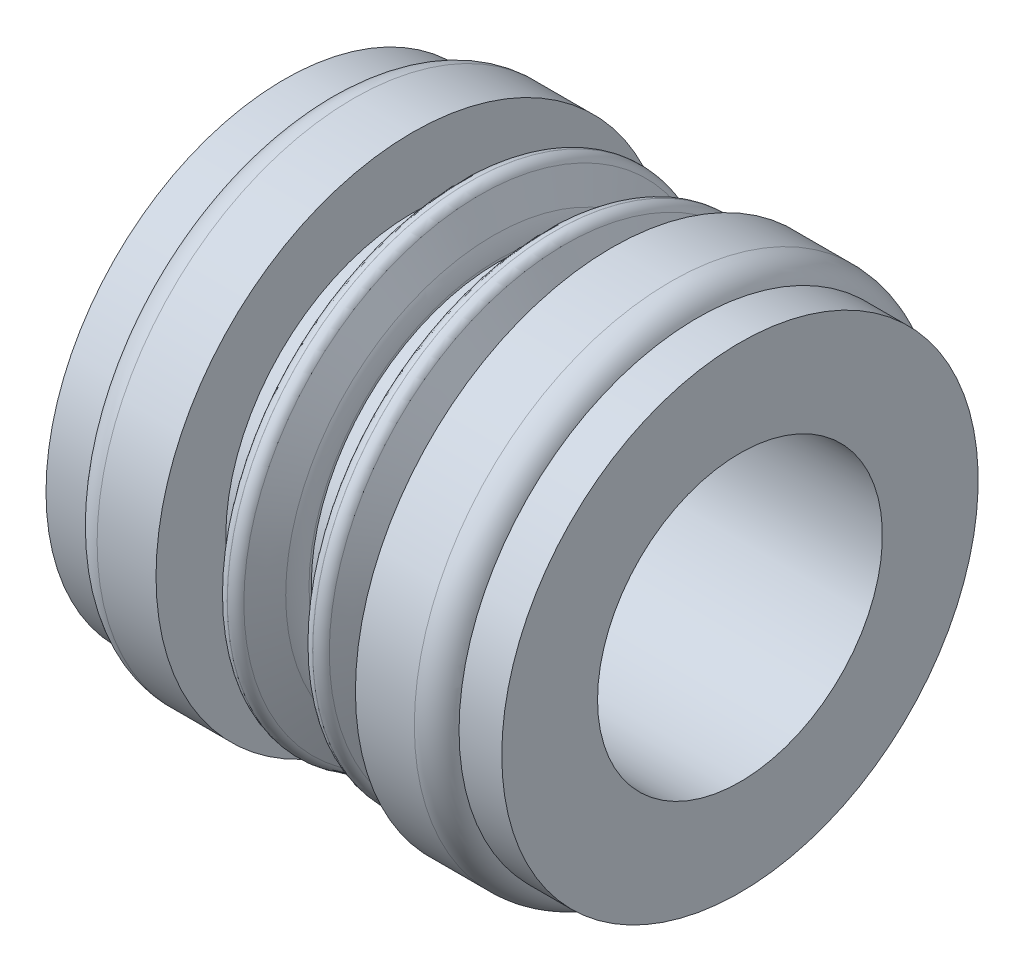
SolidWorks part; units mm, degrees
ref_plane "Front Plane" through (0, 0, 0) normal (0, 0, 1) x (1, 0, 0)
ref_plane "Top Plane" through (0, 0, 0) normal (0, 1, 0) x (1, 0, 0)
ref_plane "Right Plane" through (0, 0, 0) normal (1, 0, 0) x (0, 0, -1)
sketch "Sketch2" plane through (0, 0, 0) normal (0, 1, 0) x (1, 0, 0)
  line L0 (-34.5905, 0) -> (37.6381, 0) construction
  line L1 (-8, 5) -> (8, 5)
  line L2 (-8, 5) -> (-8, 8.3622)
  line L3 (-8, 8.3622) -> (-6.5, 8.3622)
  line L5 (-5.5679, 9) -> (-3.5, 9)
  line L6 (-3.5, 9) -> (-3.5, 6.55)
  line L7 (-3.5, 6.55) -> (-2.5, 6.55)
  line L8 (-2.5, 6.55) -> (-2.5, 6.6293)
  line L9 (-1.5013, 8.5) -> (-1.4987, 8.5)
  line L10 (-0.5, 6.6293) -> (-0.5, 6.55)
  line L11 (-0.5, 6.55) -> (0.5, 6.55)
  line L12 (0, 17.1145) -> (0, 0) construction
  line L13 (-2.3453, 7.2927) -> (-1.86, 8.2769)
  line L14 (-1.14, 8.2769) -> (-0.6547, 7.2927)
  line L15 (-2.5, 6.55) -> (-0.5, 6.55) construction
  line L16 (2.5, 6.55) -> (0.5, 6.55) construction
  line L17 (1.14, 8.2769) -> (0.6547, 7.2927)
  line L18 (2.3453, 7.2927) -> (1.86, 8.2769)
  line L19 (0.5, 6.6293) -> (0.5, 6.55)
  line L20 (1.5013, 8.5) -> (1.4987, 8.5)
  line L21 (2.5, 6.55) -> (2.5, 6.6293)
  line L22 (3.5, 6.55) -> (2.5, 6.55)
  line L23 (3.5, 9) -> (3.5, 6.55)
  line L24 (5.5679, 9) -> (3.5, 9)
  line L26 (8, 8.3622) -> (6.5, 8.3622)
  line L27 (8, 5) -> (8, 8.3622)
  arc A0 (-0.5, 6.6293) -> (-0.6547, 7.2927) centre (-2, 6.6293) ccw
  arc A1 (-2.5, 6.6293) -> (-2.3453, 7.2927) centre (-1, 6.6293) cw
  arc A2 (-1.4987, 8.5) -> (-1.14, 8.2769) centre (-1.4987, 8.1) cw
  arc A3 (-1.5013, 8.5) -> (-1.86, 8.2769) centre (-1.5013, 8.1) ccw
  arc A4 (1.5013, 8.5) -> (1.86, 8.2769) centre (1.5013, 8.1) cw
  arc A5 (1.4987, 8.5) -> (1.14, 8.2769) centre (1.4987, 8.1) ccw
  arc A6 (2.5, 6.6293) -> (2.3453, 7.2927) centre (1, 6.6293) ccw
  arc A7 (0.5, 6.6293) -> (0.6547, 7.2927) centre (2, 6.6293) cw
  arc A8 (5.5679, 9) -> (6.5, 8.3622) centre (5.5679, 8) cw
  arc A9 (-6.5, 8.3622) -> (-5.5679, 9) centre (-5.5679, 8) cw
  point P5 (0, 5)
  point P13 (-1.5, 6.55)
  point P14 (-1.5, 8.5)
  point P18 (-4.534, 9)
  point P29 (-1.25, 8.5)
  point P32 (-1.75, 8.5)
  point P47 (0, 6.55)
  point P52 (1.75, 8.5)
  point P53 (1.25, 8.5)
  point P56 (6.5, 9)
  point P59 (-6.5, 9)
  dimension "D10" = 0.5
  dimension "D12" = 1.5
  dimension "D13" = 0.4
  dimension "D14" = 1
  dimension "D1" = 16
  dimension "D2" = 5
  dimension "D3" = 9
  dimension "D5" = 1.5
  dimension "D6" = 3
  dimension "D7" = 1
  dimension "D8" = 0.5
  dimension "D9" = 0.5
  dimension "D11" = 1.55
revolve "Revolve1" add sketch "Sketch2" angle 360 about L0
